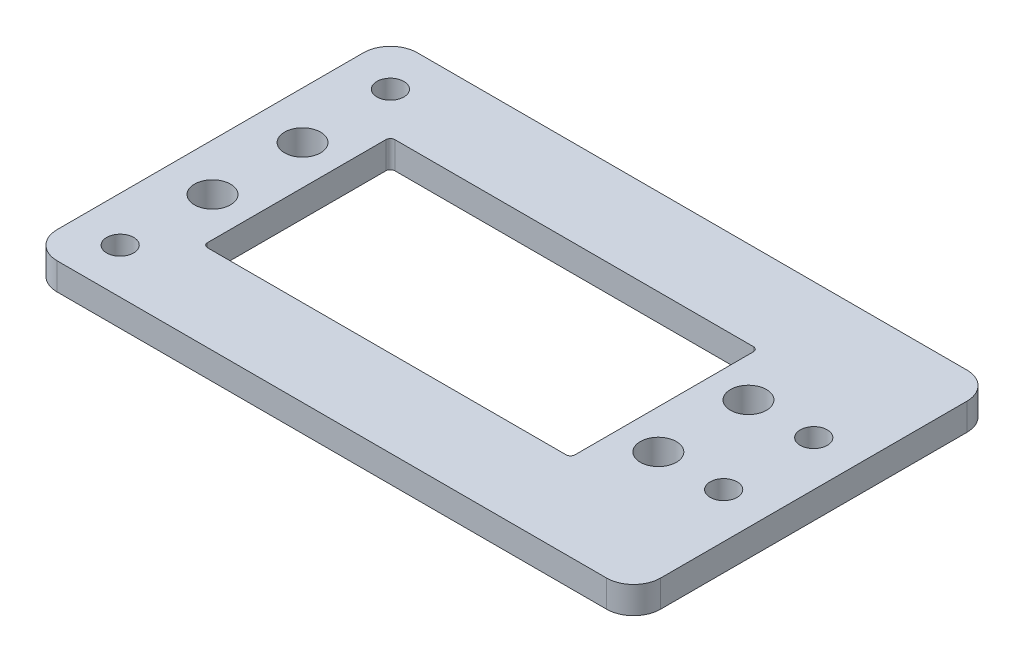
SolidWorks part; units mm, degrees
material "Thornel Mat VMA"
ref_plane "前视基准面" through (0, 0, 0) normal (0, 0, 1) x (1, 0, 0)
ref_plane "上视基准面" through (0, 0, 0) normal (0, 1, 0) x (1, 0, 0)
ref_plane "右视基准面" through (0, 0, 0) normal (1, 0, 0) x (0, 0, -1)
other "Configuration Table"
sketch "草图1" plane through (0, 0, 0) normal (0, 1, 0) x (1, 0, 0)
  line L0 (0, 0) -> (0, 29.6725) construction
  line L1 (-30, -20) -> (30, -20)
  line L2 (-30, -20) -> (-30, 20)
  line L3 (-30, 20) -> (30, 20)
  line L4 (30, -20) -> (30, 20)
  line L5 (-30, -20) -> (30, 20) construction
  line L6 (-30, 20) -> (30, -20) construction
  line L11 (-16.874, -11.2493) -> (20.241, 13.494) construction
  line L12 (30, 20) -> (37, 20)
  line L13 (-20.4, -10.4) -> (20.4, -10.4)
  line L14 (-20.4, -10.4) -> (-20.4, 10.4)
  line L15 (-20.4, 10.4) -> (20.4, 10.4)
  line L16 (20.4, -10.4) -> (20.4, 10.4)
  line L17 (-20.4, -10.4) -> (20.4, 10.4) construction
  line L18 (-20.4, 10.4) -> (20.4, -10.4) construction
  line L19 (0, 0) -> (43.0948, 0) construction
  line L20 (37, 20) -> (37, -20)
  line L21 (37, -20) -> (30, -20)
  circle A0 centre (24.75, 5) radius 2
  circle A1 centre (24.75, -5) radius 2
  circle A2 centre (-24.75, -5) radius 2
  circle A3 centre (-24.75, 5) radius 2
  circle A4 centre (-25, 15) radius 1.5
  circle A7 centre (-25, -15) radius 1.5
  circle A8 centre (32, 5) radius 1.5
  circle A9 centre (32, -5) radius 1.5
  point P0 (0, 0)
  point P6 (0, 0)
  point P13 (0, 0)
  dimension "D5" = 4
  dimension "D8" = 3
  dimension "D7" = 49.5
  dimension "D12" = 3
  dimension "D13" = 10
  dimension "D1" = 60
  dimension "D2" = 40
  dimension "D3" = 40.8
  dimension "D4" = 20.8
  dimension "D6" = 5
  dimension "D9" = 25
  dimension "D10" = 15
  dimension "D11" = 7
  dimension "D14" = 2
extrude "凸台-拉伸1" add sketch "草图1" along normal blind 3 contours L1 L4 L3 L2 A3 A2 L16 L13 L14 L15 A0 A1 A4 A7 | L21 L20 L12 L4 A8 A9
fillet "圆角1" radius 0.5 4 edges at (20.4, 1.5, 10.4) (-20.4, 1.5, 10.4) (20.4, 1.5, -10.4) (-20.4, 1.5, -10.4)
fillet "圆角2" radius 3 4 edges at (-30, 1.5, 20) (37, 1.5, 20) (37, 1.5, -20) (-30, 1.5, -20)
